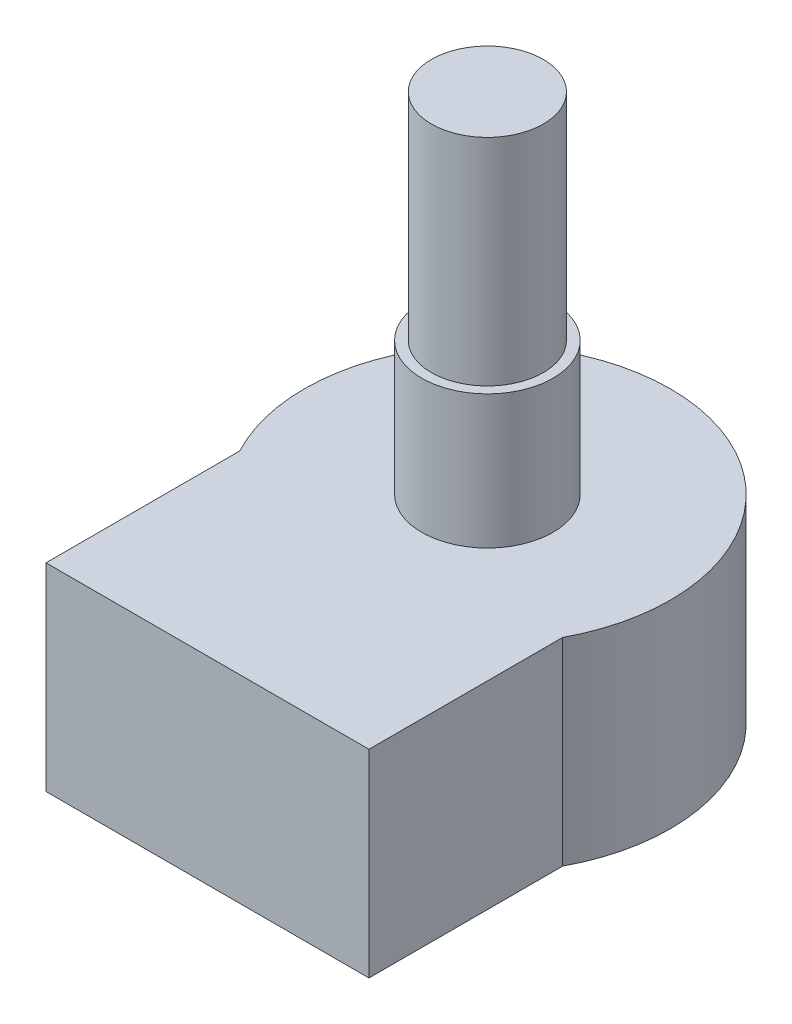
SolidWorks part; units mm, degrees
ref_plane "Front Plane" through (0, 0, 0) normal (0, 0, 1) x (1, 0, 0)
ref_plane "Top Plane" through (0, 0, 0) normal (0, 1, 0) x (1, 0, 0)
ref_plane "Right Plane" through (0, 0, 0) normal (1, 0, 0) x (0, 0, -1)
sketch "Sketch1" plane through (0, 0, 0) normal (0, 1, 0) x (1, 0, 0)
  line L1 (-7.5, -4) -> (7.5, -4)
  line L2 (-7.5, -4) -> (-7.5, -13)
  line L3 (-7.5, -13) -> (7.5, -13)
  line L4 (7.5, -4) -> (7.5, -13)
  circle A0 centre (0, 0) radius 8.5
  point P7 (0, 0)
  dimension "D1" = 17
  dimension "D2" = 15
  dimension "D3" = 13
extrude "Boss-Extrude1" add sketch "Sketch1" along normal blind 9.2 contours L1 A0 | L1 A0 | A0 L2 L3 L4
sketch "Sketch2" plane through (0, 9.2, 0) normal (0, 1, 0) x (1, 0, 0)
  circle A0 centre (0, 0) radius 3.05
  dimension "D1" = 6.1
extrude "Boss-Extrude2" add sketch "Sketch2" along normal blind 6.2 contours A0
sketch "Sketch3" plane through (0, 15.4, 0) normal (0, 1, 0) x (1, 0, 0)
  circle A0 centre (0, 0) radius 2.6
  dimension "D1" = 5.2
extrude "Boss-Extrude3" add sketch "Sketch3" along normal blind 10
